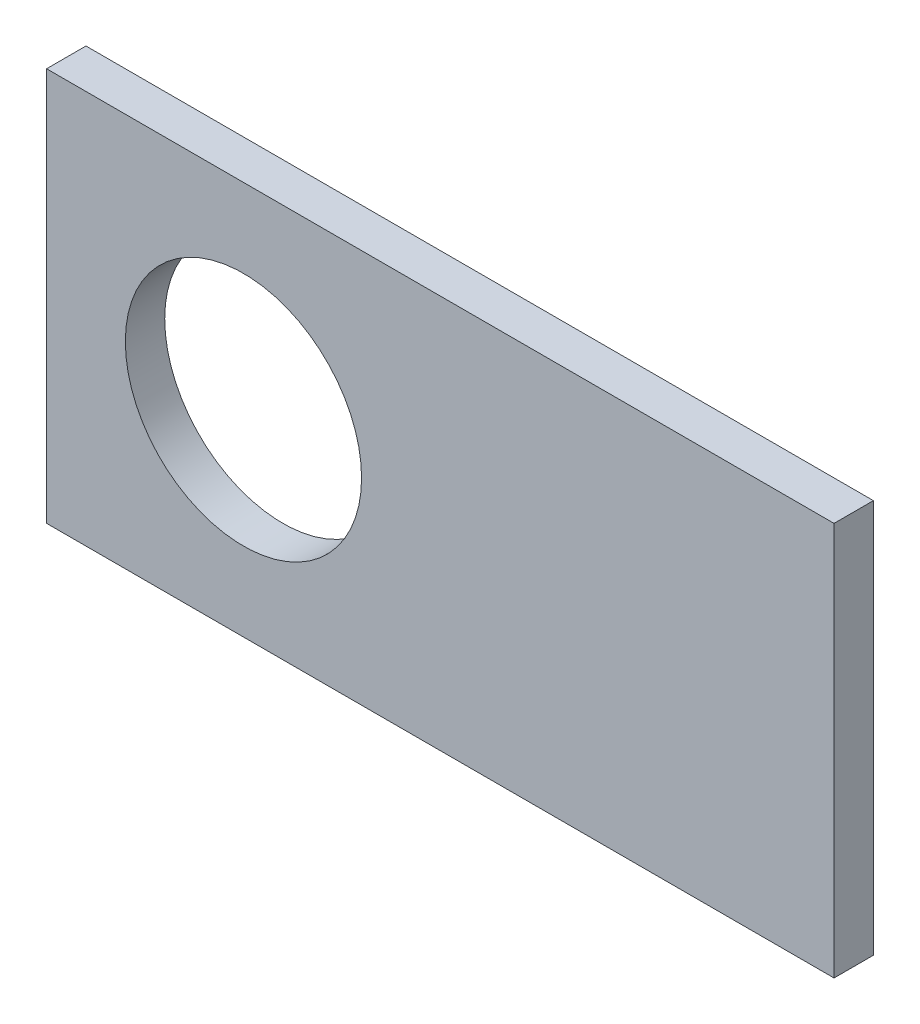
SolidWorks part; units mm, degrees
ref_plane "前视基准面" through (0, 0, 0) normal (0, 0, 1) x (1, 0, 0)
ref_plane "上视基准面" through (0, 0, 0) normal (0, 1, 0) x (1, 0, 0)
ref_plane "右视基准面" through (0, 0, 0) normal (1, 0, 0) x (0, 0, -1)
other "Configuration Table"
sketch "草图1" plane through (0, 0, 0) normal (0, 0, 1) x (1, 0, 0)
  line L1 (-50, -50) -> (50, -50)
  line L2 (-50, -50) -> (-50, 50)
  line L3 (-50, 50) -> (50, 50)
  line L5 (-50, -50) -> (50, 50) construction
  line L6 (-50, 50) -> (50, -50) construction
  line L7 (50, 50) -> (150, 50)
  line L9 (50, -50) -> (150, -50)
  line L10 (150, 50) -> (150, -50)
  circle A0 centre (0, 0) radius 30
  point P0 (0, 0)
  point P10 (0, 0)
  point P11 (50, 50)
  point P12 (44.6234, 43.3084)
  point P13 (0, 0)
  dimension "D3" = 60
  dimension "D1" = 100
  dimension "D2" = 100
  dimension "D4" = 100
extrude "凸台-拉伸1" add sketch "草图1" along normal blind 10
